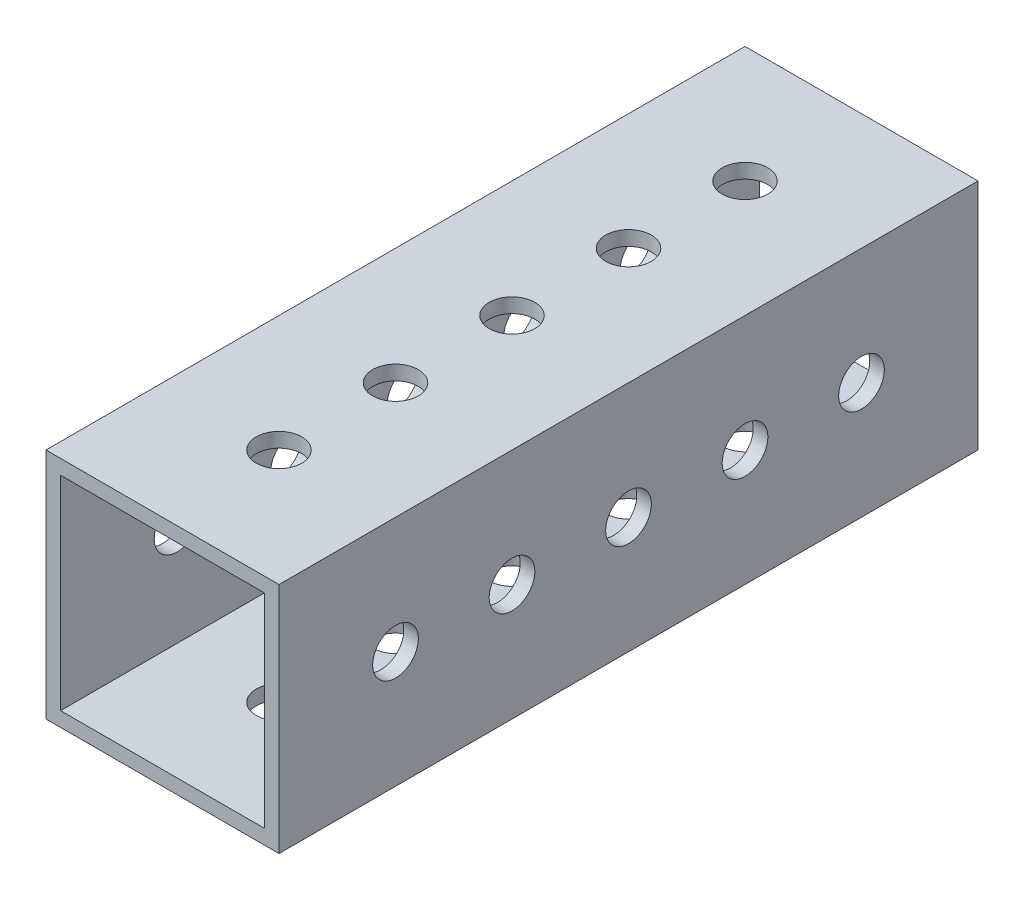
SolidWorks part; units mm, degrees
material "6061-T6 (SS)"
ref_plane "Front Plane" through (0, 0, 0) normal (0, 0, 1) x (1, 0, 0)
ref_plane "Top Plane" through (0, 0, 0) normal (0, 1, 0) x (1, 0, 0)
ref_plane "Right Plane" through (0, 0, 0) normal (1, 0, 0) x (0, 0, -1)
sketch "Sketch1" plane through (0, 0, 0) normal (0, 0, 1) x (1, 0, 0)
  line L1 (-12.7, -12.7) -> (12.7, -12.7)
  line L2 (-12.7, -12.7) -> (-12.7, 12.7)
  line L3 (-12.7, 12.7) -> (12.7, 12.7)
  line L4 (12.7, -12.7) -> (12.7, 12.7)
  line L5 (-12.7, -12.7) -> (12.7, 12.7) construction
  line L6 (-12.7, 12.7) -> (12.7, -12.7) construction
  point P0 (0, 0)
  dimension "D1" = 25.4
extrude "Boss-Extrude1" add sketch "Sketch1" along normal mid plane 76.2
shell "Shell1" thickness 1.5875
sketch "Sketch2" plane through (0, 0, 0) normal (0, 1, 0) x (1, 0, 0)
  line L0 (12.7, -38.1) -> (-12.7, -38.1) construction
  circle A0 centre (0, -25.4) radius 2.4892
  circle A2 centre (0, -12.7) radius 2.4892
  circle A3 centre (0, 0) radius 2.4892
  circle A4 centre (0, 12.7) radius 2.4892
  circle A5 centre (0, 25.4) radius 2.4892
  dimension "D1" = 4.9784
  dimension "D2" = 12.7
  dimension "D3" = 12.7
extrude "Cut-Extrude1" cut sketch "Sketch2" against normal through all both and the other way through all
sketch "Sketch3" plane through (-12.7, 0, 0) normal (-1, 0, 0) x (0, 0, 1)
  line L0 (-38.1, 12.7) -> (-38.1, -12.7) construction
  line L1 (38.1, 12.7) -> (-38.1, 12.7) construction
  circle A0 centre (-25.4, 0) radius 2.4892
  circle A1 centre (-12.7, 0) radius 2.4892
  circle A2 centre (0, 0) radius 2.4892
  circle A3 centre (12.7, 0) radius 2.4892
  circle A4 centre (25.4, 0) radius 2.4892
  point P7 (0, 0)
  point P15 (-4.7117, 0)
  dimension "D2" = 12.7
  dimension "D3" = 4.9784
  dimension "D5" = 12.7
  dimension "D1" = 12.7
  dimension "D4" = 5
extrude "Cut-Extrude2" cut sketch "Sketch3" against normal through all
